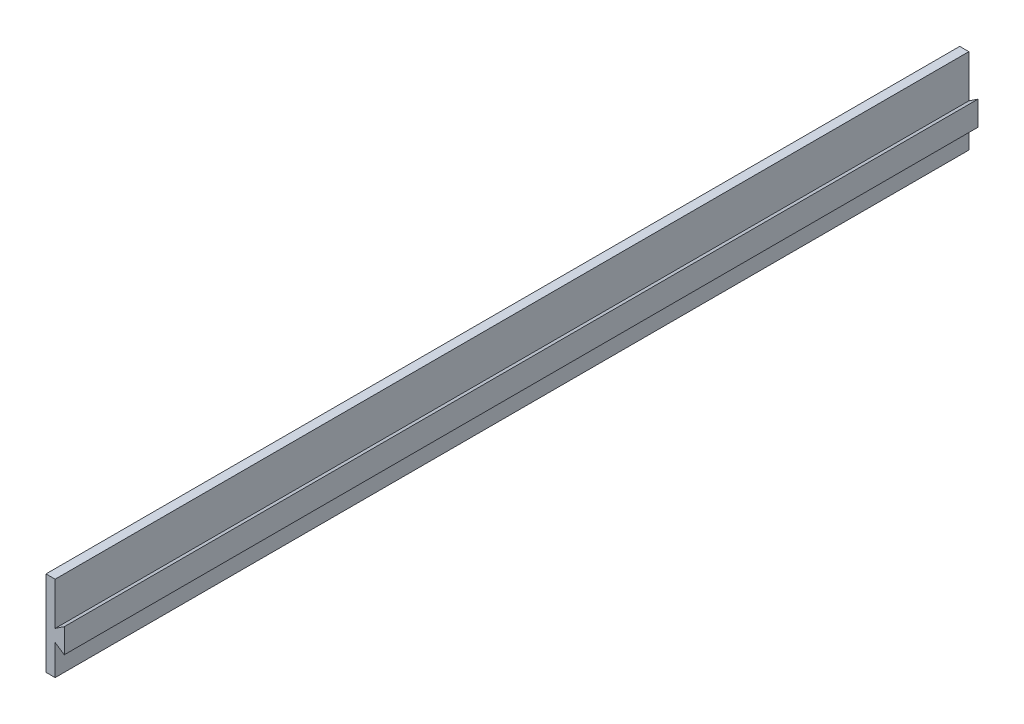
SolidWorks part; units mm, degrees
ref_plane "Front Plane" through (0, 0, 0) normal (0, 0, 1) x (1, 0, 0)
ref_plane "Top Plane" through (0, 0, 0) normal (0, 1, 0) x (1, 0, 0)
ref_plane "Right Plane" through (0, 0, 0) normal (1, 0, 0) x (0, 0, -1)
sketch "Sketch2" plane through (0, 0, 0) normal (0, 0, 1) x (1, 0, 0)
  line L0 (0, -70) -> (0, -20)
  line L1 (-15, 70) -> (0, 70)
  line L2 (-15, 70) -> (-15, -70)
  line L3 (-15, -70) -> (0, -70)
  line L4 (15, 10) -> (15, -30)
  line L5 (-15, 70) -> (15, -70) construction
  line L6 (-15, -70) -> (0, 0) construction
  line L7 (0, -20) -> (15, -30)
  line L8 (0, 70) -> (0, 0)
  line L9 (0, 0) -> (15, 10)
  point P0 (0, 0)
  dimension "D2" = 30
  dimension "D3" = 70
  dimension "D4" = 50
  dimension "D5" = 40
  dimension "D7" = 15
extrude "Boss-Extrude1" add sketch "Sketch2" along normal blind 1500
sketch "Sketch3" plane through (-15, 0, 0) normal (-1, 0, 0) x (0, 0, 1)
  line L0 (1500, -70) -> (0, -70) construction
  line L1 (0, 70) -> (0, -70) construction
  circle A0 centre (750, -60) radius 4
  dimension "D1" = 8
  dimension "D2" = 10
  dimension "D3" = 750
extrude "Boss-Extrude2" add sketch "Sketch3" along normal blind 20
